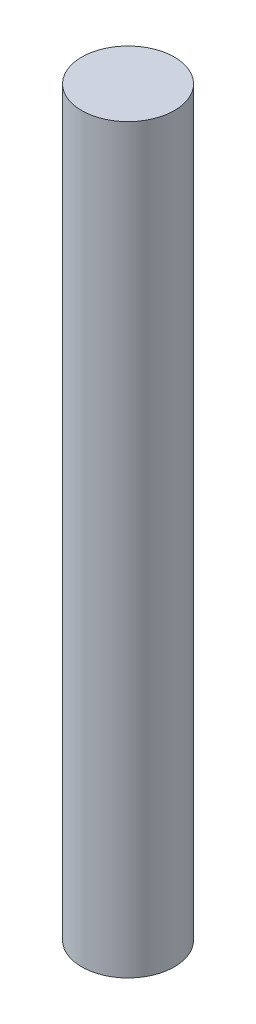
SolidWorks part; units mm, degrees
ref_plane "Front Plane" through (0, 0, 0) normal (0, 0, 1) x (1, 0, 0)
ref_plane "Top Plane" through (0, 0, 0) normal (0, 1, 0) x (1, 0, 0)
ref_plane "Right Plane" through (0, 0, 0) normal (1, 0, 0) x (0, 0, -1)
sketch "Sketch2" plane through (0, 0, 0) normal (0, 0, 1) x (1, 0, 0)
  line L0 (0, 0) -> (0, 101.6)
revolve "Revolve-Thin1" add sketch "Sketch2" angle 360 about L0 wall 6.35
